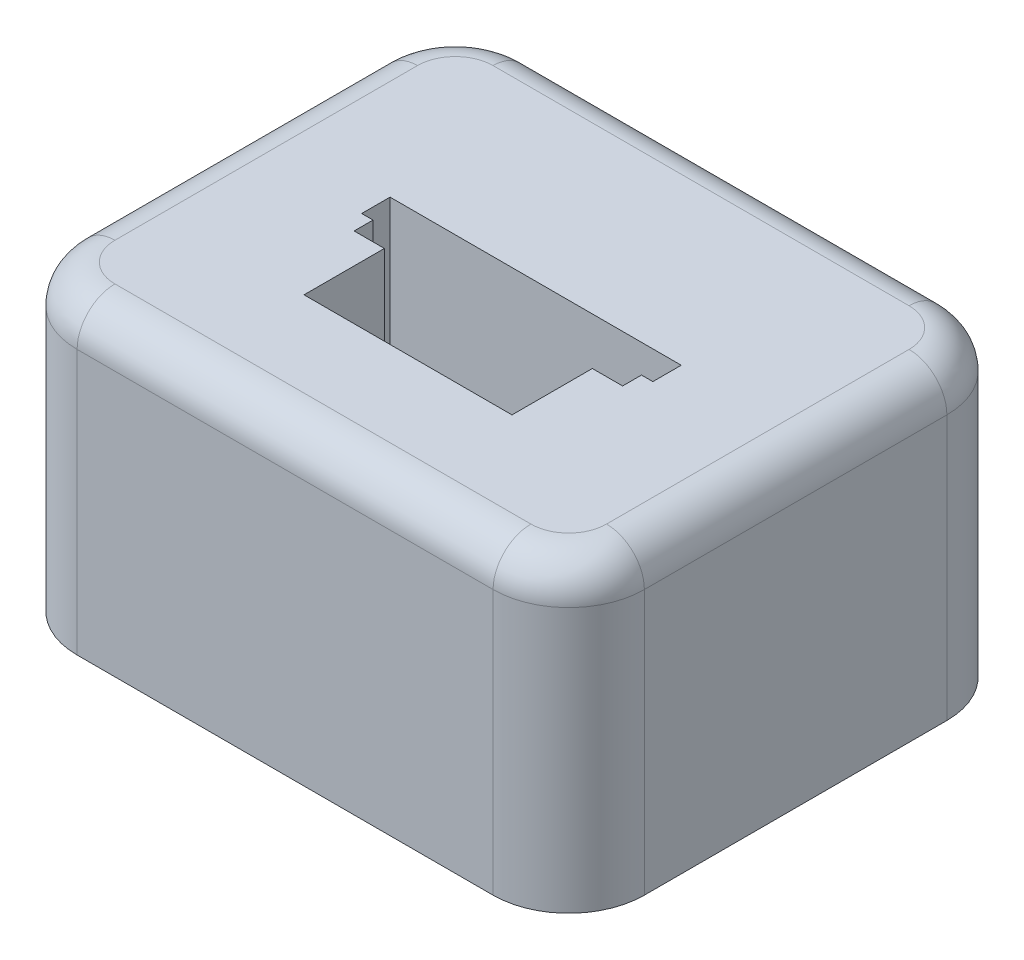
SolidWorks part; units mm, degrees
ref_plane "Спереди" through (0, 0, 0) normal (0, 0, 1) x (1, 0, 0)
ref_plane "Сверху" through (0, 0, 0) normal (0, 1, 0) x (1, 0, 0)
ref_plane "Справа" through (0, 0, 0) normal (1, 0, 0) x (0, 0, -1)
sketch "Эскиз1" plane through (0, 0, 0) normal (0, 1, 0) x (1, 0, 0)
  line L1 (4, 0) -> (26, 0)
  line L2 (0, 4) -> (0, 20)
  line L3 (4, 24) -> (26, 24)
  line L4 (30, 4) -> (30, 20)
  arc A0 (26, 24) -> (30, 20) centre (26, 20) cw
  arc A1 (26, 0) -> (30, 4) centre (26, 4) ccw
  arc A2 (4, 0) -> (0, 4) centre (4, 4) cw
  arc A3 (0, 20) -> (4, 24) centre (4, 20) cw
  point P10 (30, 0)
  point P13 (0, 0)
  point P16 (0, 24)
  dimension "D3" = 4
  dimension "D1" = 30
  dimension "D2" = 24
extrude "Тело" add sketch "Эскиз1" along normal blind 16
fillet "Скругление1" radius 2 8 edges at (15, 16, 0) (28.8284, 16, -1.1716) (1.1716, 16, -1.1716) (0, 16, -12) (1.1716, 16, -22.8284) (15, 16, -24) (28.8284, 16, -22.8284) (30, 16, -12)
sketch "Эскиз6" plane through (0, 0, 0) normal (0, -1, 0) x (1, 0, 0)
  circle A0 centre (4, -4) radius 0.9
  circle A1 centre (26, -4) radius 0.9
  circle A2 centre (26, -20) radius 0.9
  circle A3 centre (4, -20) radius 0.9
  dimension "D1" = 1.8
extrude "Крепеж" cut sketch "Эскиз6" against normal blind 7
sketch "Эскиз3" plane through (0, 16, 0) normal (0, 1, 0) x (1, 0, 0)
  line L1 (9.5, 9.5) -> (20.5, 9.5)
  line L2 (9.5, 9.5) -> (9.5, 6.5)
  line L3 (9.5, 6.5) -> (20.5, 6.5)
  line L4 (20.5, 9.5) -> (20.5, 6.5)
  line L5 (4, 0) -> (26, 0) construction
  point P7 (15, 0)
  point P11 (15, 6.5)
  dimension "D1" = 11
  dimension "D2" = 3
  dimension "D3" = 6.5
extrude "Разъем" cut sketch "Эскиз3" against normal up to next
sketch "Эскиз2" plane through (0, 16, 0) normal (0, 1, 0) x (1, 0, 0)
  line L1 (7.3, 13.25) -> (22.7, 13.25)
  line L2 (7.3, 13.25) -> (7.3, 11.75)
  line L3 (7.3, 11.75) -> (22.7, 11.75)
  line L4 (22.7, 13.25) -> (22.7, 11.75)
  line L5 (20.5, 9.5) -> (9.5, 9.5) construction
  line L6 (20.5, 6.5) -> (20.5, 9.5) construction
  point P4 (15, 11.75)
  point P9 (20.5, 8)
  point P10 (22.7, 12.5)
  point P11 (15, 9.5)
  dimension "D1" = 1.5
  dimension "D2" = 15.4
  dimension "D4" = 4.5
extrude "Плата" cut sketch "Эскиз2" against normal offset from surface (8 mm away) 8 up to face at (15, 0, -8)
sketch "Эскиз7" plane through (0, 16, 0) normal (0, 1, 0) x (1, 0, 0)
  line L0 (7.3, 11.75) -> (22.7, 11.75) construction
  line L1 (9.5, 9.5) -> (20.5, 9.5)
  line L2 (9.5, 9.5) -> (9.5, 11.75)
  line L3 (9.5, 11.75) -> (20.5, 11.75)
  line L4 (20.5, 9.5) -> (20.5, 11.75)
extrude "Вырез-Вытянуть2" cut sketch "Эскиз7" against normal offset from surface (7.5 mm away) 0.5 up to face at (15, 8, -12.5)
sketch "Эскиз8" plane through (0, 16, 0) normal (0, 1, 0) x (1, 0, 0)
  line L0 (7.3, 13.25) -> (7.3, 11.75) construction
  line L1 (7.9, 11.75) -> (22.1, 11.75)
  line L2 (7.9, 11.75) -> (7.9, 10.75)
  line L3 (7.9, 10.75) -> (22.1, 10.75)
  line L4 (22.1, 11.75) -> (22.1, 10.75)
  line L5 (22.7, 11.75) -> (22.7, 13.25) construction
  line L7 (7.3, 11.75) -> (22.7, 11.75) construction
  dimension "D1" = 0.6
  dimension "D2" = 0.6
  dimension "D3" = 1
extrude "Вырез-Вытянуть3" cut sketch "Эскиз8" against normal offset from surface (6.5 mm away) 1 up to face at (15, 8.5, -10.625)
